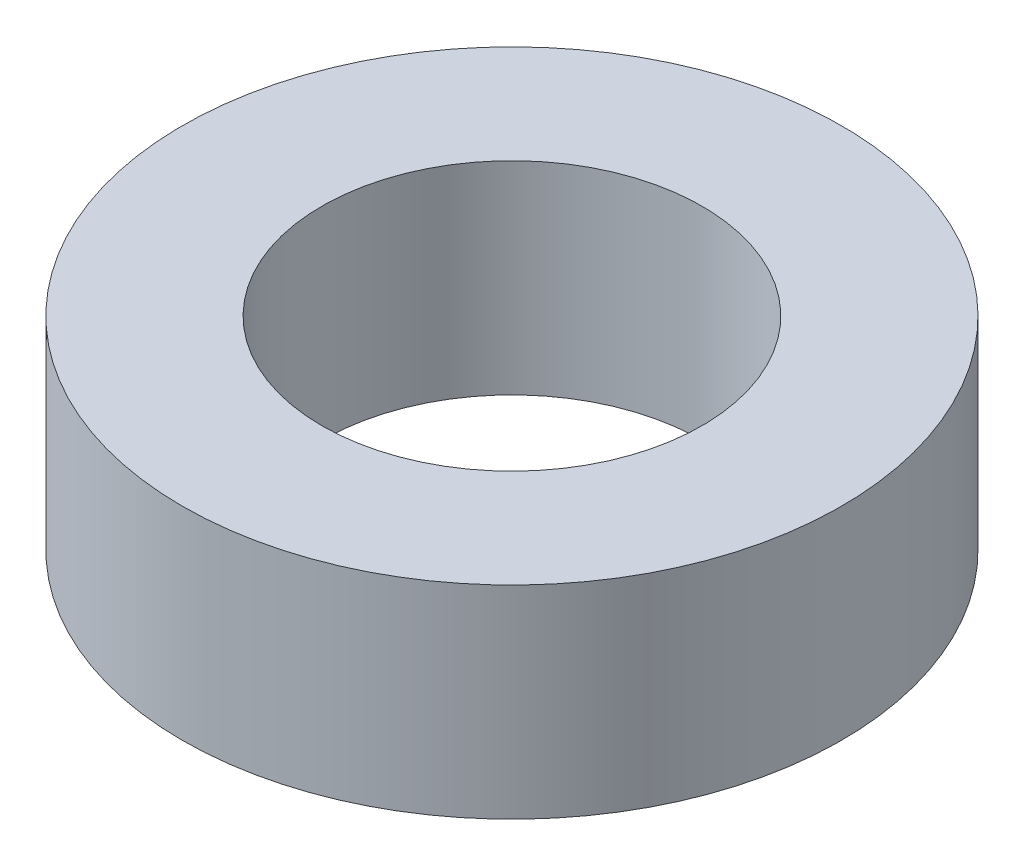
SolidWorks part; units mm, degrees
ref_plane "Front Plane" through (0, 0, 0) normal (0, 0, 1) x (1, 0, 0)
ref_plane "Top Plane" through (0, 0, 0) normal (0, 1, 0) x (1, 0, 0)
ref_plane "Right Plane" through (0, 0, 0) normal (1, 0, 0) x (0, 0, -1)
sketch "Sketch1" plane through (0, 0, 0) normal (0, 1, 0) x (1, 0, 0)
  circle A0 centre (0, 0) radius 15
  circle A1 centre (0, 0) radius 26
  dimension "D1" = 30
  dimension "D2" = 52
extrude "Boss-Extrude1" add sketch "Sketch1" along normal blind 16
